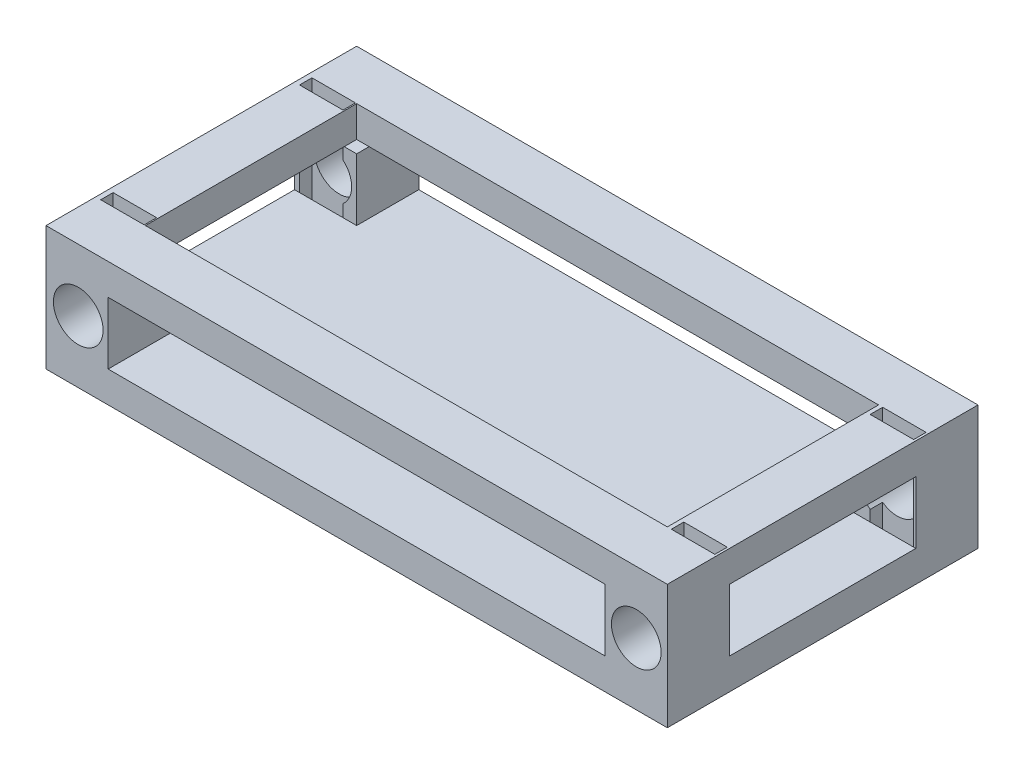
SolidWorks part; units mm, degrees
ref_plane "前视基准面" through (0, 0, 0) normal (0, 0, 1) x (1, 0, 0)
ref_plane "上视基准面" through (0, 0, 0) normal (0, 1, 0) x (1, 0, 0)
ref_plane "右视基准面" through (0, 0, 0) normal (1, 0, 0) x (0, 0, -1)
other "Configuration Table"
sketch "草图1" plane through (0, 0, 0) normal (0, 1, 0) x (1, 0, 0)
  line L0 (-26.4017, -3.1102) -> (-26.4017, 26.8898)
  line L1 (-36.4017, -13.1102) -> (63.5983, -13.1102)
  line L2 (-36.4017, -13.1102) -> (-36.4017, 36.8898)
  line L3 (-36.4017, 36.8898) -> (63.5983, 36.8898)
  line L4 (63.5983, -13.1102) -> (63.5983, 36.8898)
  line L5 (-26.4017, 26.8898) -> (53.5983, 26.8898)
  line L6 (53.5983, -3.1102) -> (53.5983, 26.8898)
  line L7 (-26.4017, -3.1102) -> (53.5983, -3.1102)
  line L9 (-26.4017, 26.8898) -> (-36.4017, 26.8898)
  line L10 (-26.4017, 26.8898) -> (-26.4017, 36.8898)
  line L11 (-26.4017, 36.8898) -> (-36.4017, 36.8898)
  line L12 (-36.4017, 26.8898) -> (-36.4017, 36.8898)
  line L13 (-26.4017, -3.1102) -> (-36.4017, -3.1102)
  line L14 (-26.4017, -3.1102) -> (-26.4017, -13.1102)
  line L15 (-26.4017, -13.1102) -> (-36.4017, -13.1102)
  line L16 (-36.4017, -3.1102) -> (-36.4017, -13.1102)
  line L17 (53.5983, -3.1102) -> (63.5983, -3.1102)
  line L18 (53.5983, -3.1102) -> (53.5983, -13.1102)
  line L19 (53.5983, -13.1102) -> (63.5983, -13.1102)
  line L20 (63.5983, -3.1102) -> (63.5983, -13.1102)
  line L21 (53.5983, 26.8898) -> (63.5983, 26.8898)
  line L22 (53.5983, 26.8898) -> (53.5983, 36.8898)
  line L23 (53.5983, 36.8898) -> (63.5983, 36.8898)
  line L24 (63.5983, 26.8898) -> (63.5983, 36.8898)
  dimension "D1" = 100
extrude "凸台-拉伸2" add sketch "草图1" along normal blind 10 contours L9 L10 L3 L2 | L14 L13 L2 L1 | L22 L21 L4 L3 | L17 L18 L1 L4
sketch "草图2" plane through (0, 0, 0) normal (0, 1, 0) x (1, 0, 0)
  line L1 (-36.4017, 36.8898) -> (63.5983, 36.8898)
  line L2 (-36.4017, 36.8898) -> (-36.4017, -13.1102)
  line L3 (-36.4017, -13.1102) -> (63.5983, -13.1102)
  line L4 (63.5983, 36.8898) -> (63.5983, -13.1102)
extrude "凸台-拉伸3" add sketch "草图2" against normal blind 5 contours L2 L1 L4 L3
sketch "草图4" plane through (0, 0, 13.1102) normal (0, 0, 1) x (1, 0, 0)
  line L1 (-36.4017, 10) -> (63.5983, 10)
  line L2 (-36.4017, 10) -> (-36.4017, 15)
  line L3 (-36.4017, 15) -> (63.5983, 15)
  line L4 (63.5983, 10) -> (63.5983, 15)
  dimension "D1" = 5
extrude "凸台-拉伸4" add sketch "草图4" against normal blind 50 contours L2 L1 L4 L3
sketch "草图7" plane through (0, 0, 13.1102) normal (0, 0, 1) x (1, 0, 0)
  circle A0 centre (-31.2094, 5) radius 4
  circle A1 centre (58.5983, 5) radius 4
extrude "切除-拉伸7" cut sketch "草图7" against normal blind 100
sketch "草图8" plane through (0, 15, 0) normal (0, 1, 0) x (1, 0, 0)
  line L14 (55.5983, -5.1102) -> (55.5983, 28.8898)
  line L15 (-28.4017, -5.1102) -> (55.5983, -5.1102)
  line L16 (-28.4017, 28.8898) -> (-28.4017, -5.1102)
  line L17 (55.5983, 28.8898) -> (-28.4017, 28.8898)
  line L18 (55.5983, -5.1102) -> (55.5983, 28.8898)
  line L19 (-28.4017, -5.1102) -> (55.5983, -5.1102)
  line L20 (-28.4017, 28.8898) -> (-28.4017, -5.1102)
  line L21 (55.5983, 28.8898) -> (-28.4017, 28.8898)
  dimension "D1" = 8
extrude "切除-拉伸9" cut sketch "草图8" against normal blind 5
sketch "草图10" plane through (0, 15, 0) normal (0, 1, 0) x (1, 0, 0)
  line L0 (-26.4017, 26.8898) -> (-36.4017, 26.8898) construction
  line L1 (-35.599, 26.8898) -> (-28.599, 26.8898)
  line L2 (-35.599, 26.8898) -> (-35.599, 28.8898)
  line L3 (-35.599, 28.8898) -> (-28.599, 28.8898)
  line L4 (-28.599, 26.8898) -> (-28.599, 28.8898)
  dimension "D1" = 7
  dimension "D2" = 2
extrude "切除-拉伸12" cut sketch "草图10" against normal up to next contours L2 L1 L4 L3
sketch "草图12" plane through (0, 15, 0) normal (0, 1, 0) x (1, 0, 0)
  line L0 (-26.4017, -3.1102) -> (-36.4017, -3.1102) construction
  line L1 (-35.599, -5.1102) -> (-28.599, -5.1102)
  line L2 (-35.599, -5.1102) -> (-35.599, -3.1102)
  line L3 (-35.599, -3.1102) -> (-28.599, -3.1102)
  line L4 (-28.599, -5.1102) -> (-28.599, -3.1102)
  line L5 (53.5983, -3.1102) -> (63.5983, -3.1102) construction
  line L6 (56.2453, 26.8898) -> (63.2453, 26.8898)
  line L7 (56.2453, 26.8898) -> (56.2453, 28.8898)
  line L8 (56.2453, 28.8898) -> (63.2453, 28.8898)
  line L9 (63.2453, 26.8898) -> (63.2453, 28.8898)
  line L10 (63.2453, -5.1102) -> (56.2453, -5.1102)
  line L11 (63.2453, -5.1102) -> (63.2453, -3.1102)
  line L12 (63.2453, -3.1102) -> (56.2453, -3.1102)
  line L13 (56.2453, -5.1102) -> (56.2453, -3.1102)
  dimension "D1" = 7
  dimension "D2" = 7
  dimension "D3" = 7
extrude "切除-拉伸13" cut sketch "草图12" against normal up to next contours L2 L1 L4 L3 | L7 L6 L9 L8 | L11 L10 L13 L12
